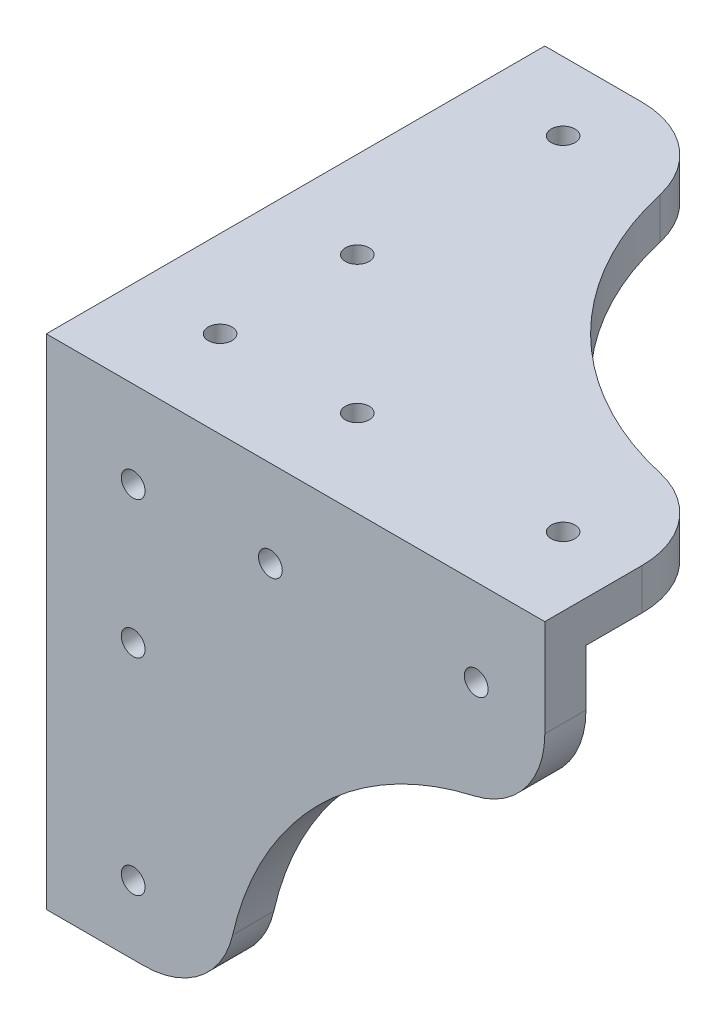
SolidWorks part; units mm, degrees
ref_plane "Front Plane" through (0, 0, 0) normal (0, 0, 1) x (1, 0, 0)
ref_plane "Top Plane" through (0, 0, 0) normal (0, 1, 0) x (1, 0, 0)
ref_plane "Right Plane" through (0, 0, 0) normal (1, 0, 0) x (0, 0, -1)
sketch "Sketch1" plane through (0, 0, 0) normal (0, 0, 1) x (1, 0, 0)
  line L0 (0, 0) -> (109, 0)
  line L1 (109, 0) -> (109, -39)
  line L2 (0, 0) -> (0, -109)
  line L3 (0, -109) -> (39, -109)
  line L4 (39, -109) -> (39, 0) construction
  line L5 (109, -39) -> (0, -39) construction
  arc A0 (39, -109) -> (109, -39) centre (109, -109) cw
  dimension "D1" = 109
  dimension "D2" = 39
extrude "Boss-Extrude1" add sketch "Sketch1" along normal blind 9
sketch "Sketch2" plane through (0, 0, 0) normal (0, 1, 0) x (1, 0, 0)
  line L0 (0, 0) -> (0, 100)
  line L1 (0, 100) -> (39, 100)
  line L2 (0, 0) -> (109, 0)
  line L3 (109, 0) -> (109, 30)
  line L4 (39, 100) -> (39, 0) construction
  line L5 (109, 0) -> (0, 0) construction
  line L6 (109, 30) -> (0, 30) construction
  arc A0 (39, 100) -> (109, 30) centre (109, 100) ccw
  dimension "D1" = 100
  dimension "D2" = 30
extrude "Boss-Extrude2" add sketch "Sketch2" against normal blind 9
sketch "Sketch3" plane through (0, 0, 0) normal (-1, 0, 0) x (0, 0, 1)
  line L0 (-30, -109) -> (0, -109)
  line L1 (0, -109) -> (0, -9)
  line L2 (0, -9) -> (-100, -9)
  line L3 (-100, -9) -> (-100, -39)
  line L4 (-100, -39) -> (0, -39) construction
  line L5 (-30, -109) -> (-30, -9) construction
  arc A0 (-100, -39) -> (-30, -109) centre (-100, -109) cw
  dimension "D1" = 30
extrude "Boss-Extrude3" add sketch "Sketch3" against normal blind 9
fillet "Fillet1" radius 20 6 edges at (4.5, -109, -30) (4.5, -39, -100) (39, -4.5, -100) (39, -109, 4.5) (109, -39, 4.5) (109, -4.5, -30)
sketch "Sketch4" plane through (0, 0, 0) normal (0, 1, 0) x (1, 0, 0)
  line L0 (19, 100) -> (19, -9) construction
  line L1 (21.2504, 100) -> (0, 100) construction
  line L2 (109, -9) -> (0, -9) construction
  line L3 (109, 10) -> (0, 10) construction
  line L4 (109, -9) -> (109, 12.2504) construction
  line L5 (0, -9) -> (0, 100) construction
  circle A0 centre (19, 85) radius 2.6
  circle A1 centre (19, 10) radius 2.6
  circle A2 centre (94, 10) radius 2.6
  circle A3 centre (49, 10) radius 2.6
  circle A4 centre (19, 40) radius 2.6
  dimension "D7" = 5.2
  dimension "D1" = 19
  dimension "D2" = 19
  dimension "D3" = 30
  dimension "D4" = 30
  dimension "D5" = 15
  dimension "D6" = 15
extrude "Cut-Extrude1" cut sketch "Sketch4" against normal through all
sketch "Sketch5" plane through (0, 0, 0) normal (-1, 0, 0) x (0, 0, 1)
  line L0 (-100, -19) -> (9, -19) construction
  line L1 (-100, -21.2504) -> (-100, 0) construction
  line L2 (9, 0) -> (9, -109) construction
  line L3 (-10, 0) -> (-10, -109) construction
  line L4 (9, 0) -> (-100, 0) construction
  line L5 (9, -109) -> (-12.2504, -109) construction
  circle A0 centre (-85, -19) radius 2.6
  circle A1 centre (-40, -19) radius 2.6
  circle A2 centre (-10, -19) radius 2.6
  circle A3 centre (-10, -49) radius 2.6
  circle A4 centre (-10, -94) radius 2.6
  dimension "D7" = 5.2
  dimension "D1" = 19
  dimension "D2" = 19
  dimension "D3" = 15
  dimension "D4" = 15
  dimension "D5" = 30
  dimension "D6" = 30
extrude "Cut-Extrude2" cut sketch "Sketch5" against normal through all
sketch "Sketch6" plane through (0, 0, 9) normal (0, 0, 1) x (1, 0, 0)
  line L0 (19, 0) -> (19, -109) construction
  line L1 (109, 0) -> (0, 0) construction
  line L2 (0, -109) -> (21.2504, -109) construction
  line L3 (0, -19) -> (109, -19) construction
  line L4 (0, 0) -> (0, -109) construction
  line L5 (109, -21.2504) -> (109, 0) construction
  circle A0 centre (19, -19) radius 2.6
  circle A1 centre (49, -19) radius 2.6
  circle A2 centre (94, -19) radius 2.6
  circle A3 centre (19, -49) radius 2.6
  circle A4 centre (19, -94) radius 2.6
  dimension "D3" = 5.2
  dimension "D4" = 15
  dimension "D5" = 15
  dimension "D7" = 30
  dimension "D1" = 19
  dimension "D2" = 19
  dimension "D6" = 30
extrude "Cut-Extrude3" cut sketch "Sketch6" against normal through all
